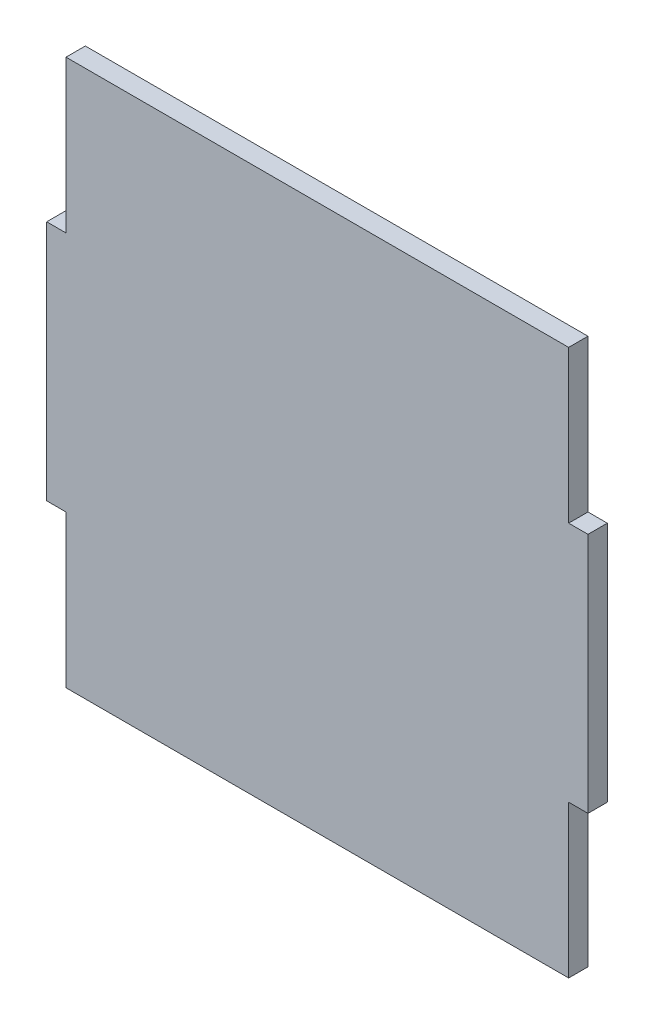
SolidWorks part; units mm, degrees
ref_plane "정면" through (0, 0, 0) normal (0, 0, 1) x (1, 0, 0)
ref_plane "윗면" through (0, 0, 0) normal (0, 1, 0) x (1, 0, 0)
ref_plane "우측면" through (0, 0, 0) normal (1, 0, 0) x (0, 0, -1)
ref_plane "평면1" through (0, 0, 40) normal (0, 0, 1) x (1, 0, 0)
sketch "스케치2" plane through (0, 0, 40) normal (0, 0, 1) x (1, 0, 0)
  line L1 (-4, -80) -> (-108, -80)
  line L2 (-4, -80) -> (-4, 83)
  line L3 (-4, 83) -> (-108, 83)
  line L4 (-108, -80) -> (-108, 83)
extrude "보스-돌출1" add sketch "스케치2" along normal blind 4
sketch "스케치3" plane through (0, 0, 40) normal (0, 0, -1) x (-1, 0, 0)
  line L0 (4, 87) -> (4, -80.15) construction
  line L1 (4, 48.3) -> (108, 48.3)
  line L2 (4, 48.3) -> (4, -54.3)
  line L3 (4, -54.3) -> (108, -54.3)
  line L4 (108, 48.3) -> (108, -54.3)
  line L5 (108, 83) -> (108, -80) construction
  dimension "D1" = 102.6
sketch "스케치4" plane through (0, 0, 40) normal (0, 0, -1) x (-1, 0, 0)
  line L6 (4, 53.5) -> (108, 53.5)
  line L7 (4, 53.5) -> (108, 53.5)
  line L9 (4, -59.5) -> (108, -59.5)
  line L10 (4, -59.5) -> (108, -59.5)
  line M3 (4, 83) -> (4, -80)
  line M4 (4, -80) -> (108, -80)
  line M5 (108, -80) -> (108, 83)
  line M6 (108, 83) -> (4, 83)
  dimension "D1" = 5.2
  dimension "D2" = 5.2
extrude "컷-돌출1" cut sketch "스케치4" against normal blind 4 contours L7 M3 M5 M6 | L10 M3 M4 M5
sketch "스케치5" plane through (-108, 0, 0) normal (-1, 0, 0) x (0, 0, 1)
  line L0 (40, 48.3) -> (40, -54.3) construction
  line L1 (40, -28) -> (44, -28)
  line L2 (40, -28) -> (40, 22)
  line L3 (40, 22) -> (44, 22)
  line L4 (44, -28) -> (44, 22)
  line L5 (40, -28) -> (44, -28) construction
  line L6 (44, 53.5) -> (44, -59.5) construction
  line L7 (44, 22) -> (40, 22) construction
extrude "보스-돌출2" add sketch "스케치5" along normal blind 4
sketch "스케치7" plane through (-4, 0, 0) normal (1, 0, 0) x (0, 0, -1)
  line L1 (-40, 22) -> (-44, 22)
  line L2 (-40, 22) -> (-40, -28)
  line L3 (-40, -28) -> (-44, -28)
  line L4 (-44, 22) -> (-44, -28)
extrude "보스-돌출3" add sketch "스케치7" along normal blind 4
